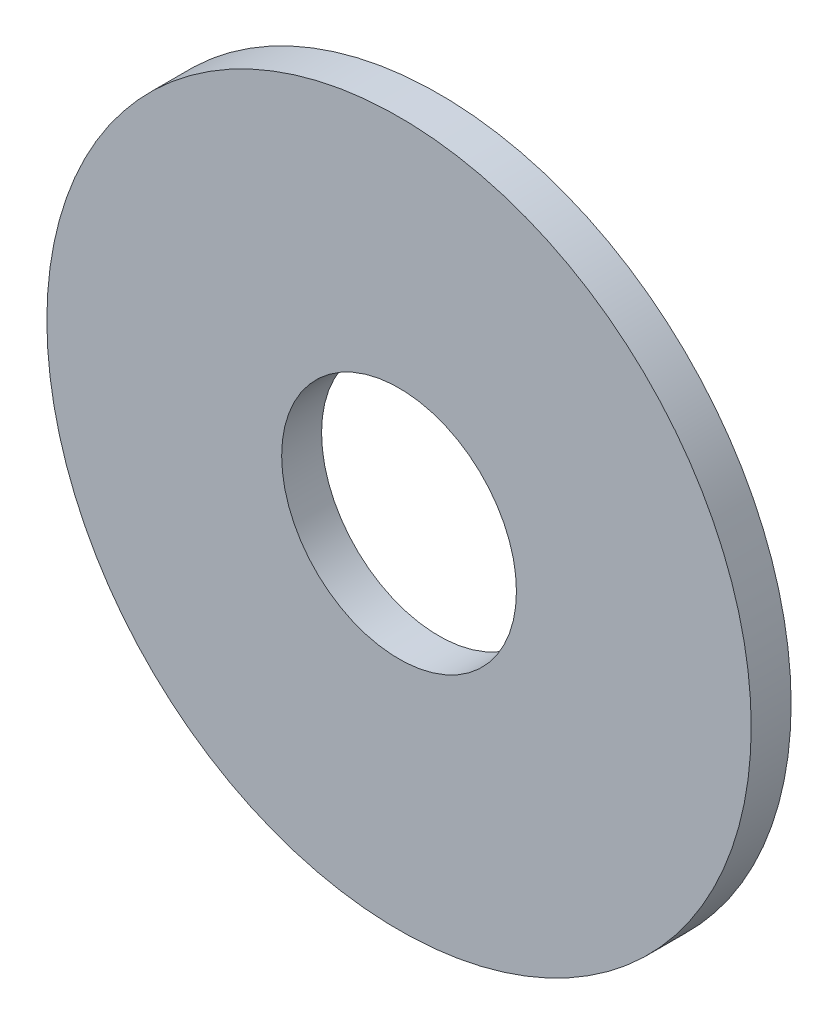
SolidWorks part; units mm, degrees
material "ABS PC"
ref_plane "Front Plane" through (0, 0, 0) normal (0, 0, 1) x (1, 0, 0)
ref_plane "Top Plane" through (0, 0, 0) normal (0, 1, 0) x (1, 0, 0)
ref_plane "Right Plane" through (0, 0, 0) normal (1, 0, 0) x (0, 0, -1)
sketch "Sketch1" plane through (0, 0, 0) normal (0, 0, 1) x (1, 0, 0)
  circle A0 centre (0, 0) radius 15
  circle A1 centre (0, 0) radius 5
  dimension "D1" = 30
  dimension "D2" = 10
extrude "Boss-Extrude1" add sketch "Sketch1" along normal blind 1.7
equation "\"smallPulleyTeeth\"= 15"
equation "\"largePulleyTeeth\"= 30"
equation "\"eighthThick\"= 2.9mm"
equation "\"sixteenthThick\"= 1.7mm"
equation "\"wheelEighthThick\"=3.0mm"
equation "\"quarterThick\"=5.6mm"
equation "\"bushingDiam\"= 7.85mm"
equation "\"plateBoltCircle\"= 65mm"
equation "\"plateBoltDiam\"= 5mm"
equation "\"D1@Boss-Extrude1\"=\"sixteenthThick\""
